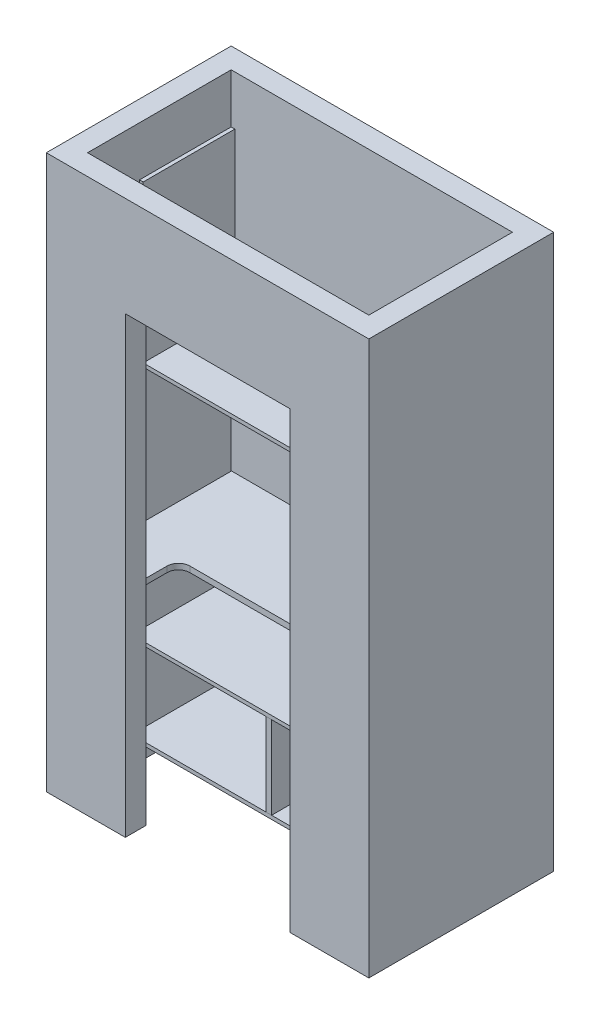
SolidWorks part; units mm, degrees
ref_plane "Front" through (0, 0, 0) normal (0, 0, 1) x (1, 0, 0)
ref_plane "Top" through (0, 0, 0) normal (0, 1, 0) x (1, 0, 0)
ref_plane "Right" through (0, 0, 0) normal (1, 0, 0) x (0, 0, -1)
sketch "Sketch1" plane through (0, 0, 0) normal (0, 1, 0) x (1, 0, 0)
  line L0 (-90, 90) -> (1318, 90)
  line L1 (0, 0) -> (1228, 0)
  line L2 (0, 0) -> (0, -627)
  line L3 (0, -627) -> (255, -627)
  line L4 (1228, 0) -> (1228, -627)
  line L5 (1318, 90) -> (1318, -717)
  line L6 (-90, -717) -> (255, -717)
  line L7 (-90, 90) -> (-90, -717)
  line L8 (255, -627) -> (255, -717)
  line L9 (973, -627) -> (973, -717)
  line L10 (973, -717) -> (1318, -717)
  line L11 (973, -627) -> (1228, -627)
  line L12 (-90, -717) -> (1318, -717) construction
  line L13 (255, -627) -> (973, -627)
  line L14 (0, -627) -> (1228, -627) construction
  line L15 (255, -717) -> (973, -717)
  dimension "D1" = 1228
  dimension "D2" = 627
  dimension "D4" = 255
  dimension "D5" = 255
  dimension "D3" = 90
extrude "Boss-Extrude1" add sketch "Sketch1" along normal blind 2416 contours L11 L9 L10 L5 L0 L7 L6 L8 L3 L2 L1 L4 | L8 L15 L9 L13
sketch "Sketch2" plane through (0, 0, 717) normal (0, 0, 1) x (1, 0, 0)
  line L0 (-90, 0) -> (1318, 0) construction
  line L1 (255, 0) -> (973, 0)
  line L2 (255, 0) -> (255, 1980)
  line L3 (255, 1980) -> (973, 1980)
  line L4 (973, 0) -> (973, 1980)
  line L5 (0, 2416) -> (0, 0) construction
  line L6 (1228, 2416) -> (1228, 0) construction
  dimension "D1" = 255
  dimension "D2" = 255
  dimension "D3" = 1980
  dimension "D4" = 718
extrude "Cut-Extrude1" cut sketch "Sketch2" against normal blind 100
sketch "Sketch4" plane through (0, 0, 0) normal (0, 0, 1) x (1, 0, 0)
  line L5 (0, 120) -> (1228, 120)
  line L7 (16, 136) -> (1212, 136)
  line L9 (16, 513.5) -> (601.5, 513.5)
  line L11 (16, 497.5) -> (601.5, 497.5)
  line L13 (16, 875) -> (1212, 875)
  line L15 (16, 900) -> (1212, 900)
  line L21 (16, 1500) -> (1212, 1500)
  line L23 (16, 1516) -> (1212, 1516)
  line L25 (16, 1766) -> (1212, 1766)
  line L27 (16, 1782) -> (1212, 1782)
  line L37 (626.5, 513.5) -> (1212, 513.5)
  line L38 (626.5, 497.5) -> (1212, 497.5)
  line L39 (16, 1500) -> (0, 1500)
  line L40 (0, 120) -> (16, 120)
  line L41 (0, 120) -> (0, 2320)
  line L42 (598, 120) -> (614, 120)
  line L43 (601.5, 136) -> (601.5, 875)
  line L44 (601.5, 875) -> (614, 875)
  line L46 (614, 875) -> (626.5, 875)
  line L48 (614, 120) -> (630, 120)
  line L49 (626.5, 875) -> (626.5, 136)
  line L50 (0, 2320) -> (16, 2320)
  line L51 (16, 120) -> (16, 2320)
  line L52 (1212, 1500) -> (1228, 1500)
  line L54 (1228, 2320) -> (1228, 120)
  line L56 (1212, 2320) -> (1212, 120)
  line L57 (614, 136) -> (614, 171.2625) construction
  line L58 (1212, 2320) -> (1228, 2320)
  line L59 (-90, 0) -> (255, 0) construction
  line L60 (308.75, 513.5) -> (308.75, 875) construction
  line L61 (308.75, 497.5) -> (308.75, 136) construction
  point P11 (0, 0)
  point P12 (614, 875)
  dimension "D2" = 120
  dimension "D4" = 16
  dimension "D5" = 25
  dimension "D6" = 12.5
  dimension "D3" = 25
  dimension "D7" = 1500
  dimension "D8" = 250
  dimension "D9" = 16
  dimension "D10" = 2200
  dimension "D11" = 16
  dimension "D12" = 16
  dimension "D13" = 16
  dimension "D14" = 16
  dimension "D15" = 900
sketch "Sketch5" plane through (0, 0, 0) normal (0, 0, 1) x (1, 0, 0)
  line L0 (0, 120) -> (0, 2320) construction
  line L1 (-1606.3267, 2611.8064) -> (-1006.3267, 2611.8064)
  line L2 (-1606.3267, 2611.8064) -> (-1606.3267, 411.8064)
  line L3 (-1606.3267, 411.8064) -> (-1006.3267, 411.8064)
  line L4 (-1006.3267, 2611.8064) -> (-1006.3267, 411.8064)
  line L5 (2423.9275, 2306.3788) -> (3023.9275, 2306.3788)
  line L6 (2423.9275, 2306.3788) -> (2423.9275, 106.3788)
  line L7 (2423.9275, 106.3788) -> (3023.9275, 106.3788)
  line L8 (3023.9275, 2306.3788) -> (3023.9275, 106.3788)
  line L9 (3143.9275, 2306.3788) -> (3643.9275, 2306.3788)
  line L10 (3143.9275, 2306.3788) -> (3143.9275, 1110.3788)
  line L11 (3143.9275, 1110.3788) -> (3643.9275, 1110.3788)
  line L12 (3643.9275, 2306.3788) -> (3643.9275, 1110.3788)
  line L13 (-975.7534, 2611.8064) -> (-475.7534, 2611.8064)
  line L14 (-975.7534, 2611.8064) -> (-975.7534, 1415.8064)
  line L15 (-975.7534, 1415.8064) -> (-475.7534, 1415.8064)
  line L16 (-475.7534, 2611.8064) -> (-475.7534, 1415.8064)
  line L17 (3143.9275, 1069.7068) -> (3643.9275, 1069.7068)
  line L18 (3143.9275, 1069.7068) -> (3143.9275, 484.2068)
  line L19 (3143.9275, 484.2068) -> (3643.9275, 484.2068)
  line L20 (3643.9275, 1069.7068) -> (3643.9275, 484.2068)
  line L21 (3143.9275, 451.8788) -> (3643.9275, 451.8788)
  line L22 (3143.9275, 451.8788) -> (3143.9275, -133.6212)
  line L23 (3143.9275, -133.6212) -> (3643.9275, -133.6212)
  line L24 (3643.9275, 451.8788) -> (3643.9275, -133.6212)
  line L25 (-975.7534, 1365.5983) -> (-475.7534, 1365.5983)
  line L26 (-975.7534, 1365.5983) -> (-975.7534, 780.0983)
  line L27 (-975.7534, 780.0983) -> (-475.7534, 780.0983)
  line L28 (-475.7534, 1365.5983) -> (-475.7534, 780.0983)
  line L29 (-975.7534, 752.1804) -> (-475.7534, 752.1804)
  line L30 (-975.7534, 752.1804) -> (-975.7534, 166.6804)
  line L31 (-975.7534, 166.6804) -> (-475.7534, 166.6804)
  line L32 (-475.7534, 752.1804) -> (-475.7534, 166.6804)
  line L33 (16, 1766) -> (1212, 1766) construction
  line L34 (16, 513.5) -> (601.5, 513.5) construction
  line L35 (601.5, 136) -> (601.5, 875) construction
  line L36 (478.6269, 3575.8977) -> (978.6269, 3575.8977)
  line L37 (478.6269, 3575.8977) -> (478.6269, 2836.8977)
  line L38 (478.6269, 2836.8977) -> (978.6269, 2836.8977)
  line L39 (978.6269, 3575.8977) -> (978.6269, 2836.8977)
  line L40 (-116.3423, 3579.4372) -> (383.6577, 3579.4372)
  line L41 (-116.3423, 3579.4372) -> (-116.3423, 2840.4372)
  line L42 (-116.3423, 2840.4372) -> (383.6577, 2840.4372)
  line L43 (383.6577, 3579.4372) -> (383.6577, 2840.4372)
  dimension "D1" = 500
  dimension "D2" = 600
  dimension "D3" = 2440
  dimension "D4" = 1220
sketch "Sketch6" plane through (0, 0, 0) normal (0, 0, 1) x (1, 0, 0)
  line L0 (0, 120) -> (0, 2320) construction
  line L13 (16, 875) -> (0, 875)
  line L14 (16, 875) -> (16, 136)
  line L15 (16, 136) -> (0, 136)
  line L16 (0, 875) -> (0, 136)
  line L17 (16, 136) -> (1212, 136) construction
  line L18 (1228, 2320) -> (1228, 120) construction
  line L19 (1212, 875) -> (1228, 875)
  line L20 (1212, 875) -> (1212, 136)
  line L21 (1212, 136) -> (1228, 136)
  line L22 (1228, 875) -> (1228, 136)
  line L24 (601.5, 497.5) -> (626.5, 497.5)
  line L25 (601.5, 497.5) -> (601.5, 136)
  line L26 (601.5, 136) -> (626.5, 136)
  line L27 (626.5, 497.5) -> (626.5, 136)
  point P4 (0, 0)
  point P5 (601.5, 497.5)
extrude "Boss-Extrude2" add sketch "Sketch6" along normal blind 625 separate body
sketch "Sketch7" plane through (0, 0, 0) normal (0, 0, 1) x (1, 0, 0)
  line L0 (1228, 2320) -> (1228, 120) construction
  line L1 (0, 120) -> (1228, 120)
  line L2 (0, 120) -> (0, 136)
  line L3 (0, 136) -> (1228, 136)
  line L4 (1228, 120) -> (1228, 136)
  line L5 (16, 497.5) -> (626.5, 497.5)
  line L6 (16, 497.5) -> (16, 513.5)
  line L7 (16, 513.5) -> (601.5, 513.5)
  line L9 (626.5, 497.5) -> (1212, 497.5)
  line L11 (601.5, 513.5) -> (1212, 513.5)
  line L12 (1212, 497.5) -> (1212, 513.5)
  line L13 (0, 875) -> (1228, 875)
  line L14 (0, 875) -> (0, 900)
  line L15 (0, 900) -> (1228, 900)
  line L16 (1228, 875) -> (1228, 900)
  line L17 (16, 900) -> (1212, 900) construction
  point P14 (625.1308, 497.5)
  point P27 (599.8528, 513.5)
extrude "Boss-Extrude3" add sketch "Sketch7" along normal blind 450 separate body
sketch "Sketch8" plane through (0, 0, 0) normal (0, 0, 1) x (1, 0, 0)
  line L0 (0, 120) -> (0, 2320) construction
  line L1 (16, 1500) -> (0, 1500)
  line L2 (16, 1500) -> (16, 2200)
  line L3 (16, 2200) -> (0, 2200)
  line L4 (0, 1500) -> (0, 2200)
  line L5 (1228, 2320) -> (1228, 120) construction
  line L6 (1212, 1500) -> (1228, 1500)
  line L7 (1212, 1500) -> (1212, 2200)
  line L8 (1212, 2200) -> (1228, 2200)
  line L9 (1228, 1500) -> (1228, 2200)
  dimension "D1" = 700
extrude "Boss-Extrude4" add sketch "Sketch8" along normal blind 400 separate body
sketch "Sketch9" plane through (0, 0, 0) normal (0, 0, 1) x (1, 0, 0)
  line L1 (16, 1782) -> (1212, 1782)
  line L2 (16, 1782) -> (16, 1766)
  line L3 (16, 1766) -> (1212, 1766)
  line L4 (1212, 1782) -> (1212, 1766)
  line L5 (16, 1516) -> (1212, 1516)
  line L6 (16, 1516) -> (16, 1500)
  line L7 (16, 1500) -> (1212, 1500)
  line L8 (1212, 1516) -> (1212, 1500)
extrude "Boss-Extrude5" add sketch "Sketch9" along normal blind 400 separate body
sketch "Sketch11" plane through (0, 900, 0) normal (0, 1, 0) x (1, 0, 0)
  line L0 (0, -450) -> (0, -627)
  line L1 (0, -627) -> (220, -627)
  line L2 (0, -627) -> (1228, -627) construction
  line L3 (220, -627) -> (220, -450)
  line L4 (1228, -450) -> (0, -450) construction
  line L5 (614, 90) -> (614, 254.9806) construction
  line L6 (-90, 90) -> (1318, 90) construction
  line L7 (0, -450) -> (220, -450)
  line L8 (1228, -450) -> (1008, -450)
  line L9 (1008, -627) -> (1008, -450)
  line L10 (1228, -627) -> (1008, -627)
  line L11 (1228, -450) -> (1228, -627)
  dimension "D1" = 220
extrude "Boss-Extrude6" add sketch "Sketch11" against normal up to surface (25 mm away) up to face at (614, 875, 225)
fillet "Fillet1" radius 50 2 edges at (220, 887.5, 450) (1008, 887.5, 450)
sketch "Sketch12" plane through (0, 0, 625) normal (0, 0, 1) x (1, 0, 0)
  line L4 (601.5, 497.5) -> (601.5, 136)
  line L5 (601.5, 136) -> (626.5, 136)
  line L6 (626.5, 136) -> (626.5, 497.5)
  line L7 (626.5, 497.5) -> (601.5, 497.5)
  line L8 (601.5, 497.5) -> (601.5, 136)
  line L9 (601.5, 136) -> (626.5, 136)
  line L10 (626.5, 136) -> (626.5, 497.5)
  line L11 (626.5, 497.5) -> (601.5, 497.5)
  dimension "D1" = 0
extrude "Cut-Extrude2" cut sketch "Sketch12" against normal up to surface (175 mm away) up to face at (614, 128, 450)
sketch "Sketch13" plane through (0, 120, 0) normal (0, -1, 0) x (1, 0, 0)
  line L4 (0, 627) -> (0, 450)
  line L5 (220, 627) -> (0, 627)
  line L6 (220, 450) -> (220, 627)
  line L7 (0, 450) -> (220, 450)
  line L8 (0, 627) -> (0, 450)
  line L9 (220, 627) -> (0, 627)
  line L10 (220, 450) -> (220, 627)
  line L11 (0, 450) -> (220, 450)
  line L12 (1228, 627) -> (1008, 627)
  line L13 (1228, 450) -> (1228, 627)
  line L14 (1008, 450) -> (1228, 450)
  line L15 (1008, 627) -> (1008, 450)
  line L16 (1228, 627) -> (1008, 627)
  line L17 (1228, 450) -> (1228, 627)
  line L18 (1008, 450) -> (1228, 450)
  line L19 (1008, 627) -> (1008, 450)
  dimension "D1" = 0
  dimension "D2" = 0
extrude "Boss-Extrude7" [suppressed] add sketch "Sketch13" against normal up to surface (16 mm away)
sketch "Sketch14" plane through (0, 513.5, 0) normal (0, 1, 0) x (1, 0, 0)
  line L4 (1008, -627) -> (1228, -627)
  line L5 (1008, -450) -> (1008, -627)
  line L6 (1228, -450) -> (1008, -450)
  line L7 (1228, -627) -> (1228, -450)
  line L8 (1008, -627) -> (1228, -627)
  line L9 (1008, -450) -> (1008, -627)
  line L10 (1228, -450) -> (1008, -450)
  line L11 (1228, -627) -> (1228, -450)
  line L12 (0, -450) -> (0, -627)
  line L13 (220, -450) -> (0, -450)
  line L14 (220, -627) -> (220, -450)
  line L15 (0, -627) -> (220, -627)
  line L16 (0, -450) -> (0, -627)
  line L17 (220, -450) -> (0, -450)
  line L18 (220, -627) -> (220, -450)
  line L19 (0, -627) -> (220, -627)
  dimension "D1" = 0
  dimension "D2" = 0
extrude "Boss-Extrude8" [suppressed] add sketch "Sketch14" against normal up to surface (16 mm away)
fillet "Fillet2" [suppressed] radius 50
fillet "Fillet3" [suppressed] radius 50
fillet "Fillet4" [suppressed] radius 50
sketch "Sketch15" [suppressed] plane through (0, 513.5, 0) normal (0, 1, 0) x (1, 0, 0)
  line L1 (16, -450) -> (0, -450)
  line L2 (16, -450) -> (16, -627)
  line L3 (16, -627) -> (0, -627)
  line L4 (0, -450) -> (0, -627)
  line L5 (1212, -450) -> (1228, -450)
  line L6 (1212, -450) -> (1212, -627)
  line L7 (1212, -627) -> (1228, -627)
  line L8 (1228, -450) -> (1228, -627)
extrude "Cut-Extrude3" [suppressed] cut sketch "Sketch15" against normal blind 500
sketch "Sketch17" plane through (16, 0, 0) normal (1, 0, 0) x (0, 0, -1)
  line L0 (-625, 136) -> (0, 136) construction
  line L1 (-450, 136) -> (-625, 136)
  line L2 (-450, 136) -> (-450, 775)
  line L3 (-500, 825) -> (-625, 825)
  line L4 (-625, 136) -> (-625, 825)
  line L5 (-625, 136) -> (-625, 875) construction
  line L6 (-625, 875) -> (0, 875) construction
  line L7 (-450, 513.5) -> (-450, 497.5) construction
  arc A0 (-450, 775) -> (-500, 825) centre (-500, 775) ccw
  dimension "D1" = 50
  dimension "D2" = 50
extrude "Cut-Extrude4" [suppressed] cut sketch "Sketch17" against normal through all both and the other way through all
sketch "Sketch18" plane through (0, 120, 0) normal (0, -1, 0) x (1, 0, 0)
  line L0 (16, 0) -> (1212, 0) construction
  line L1 (0, 627) -> (1.5, 627)
  line L2 (0, 627) -> (0, 0)
  line L3 (0, 0) -> (1.5, 0)
  line L4 (1.5, 627) -> (1.5, 0)
  line L5 (1.5, 73.7952) -> (1226.5, 73.7952) construction
  line L6 (1228, 627) -> (1226.5, 627)
  line L7 (1228, 627) -> (1228, 0)
  line L8 (1228, 0) -> (1226.5, 0)
  line L9 (1226.5, 627) -> (1226.5, 0)
  line L10 (614, 73.7952) -> (614, -90) construction
  line L11 (-90, -90) -> (1318, -90) construction
  point P18 (0, 627)
  point P19 (1228, 627)
  dimension "D1" = 1225
extrude "Cut-Extrude5" cut sketch "Sketch18" against normal through all
